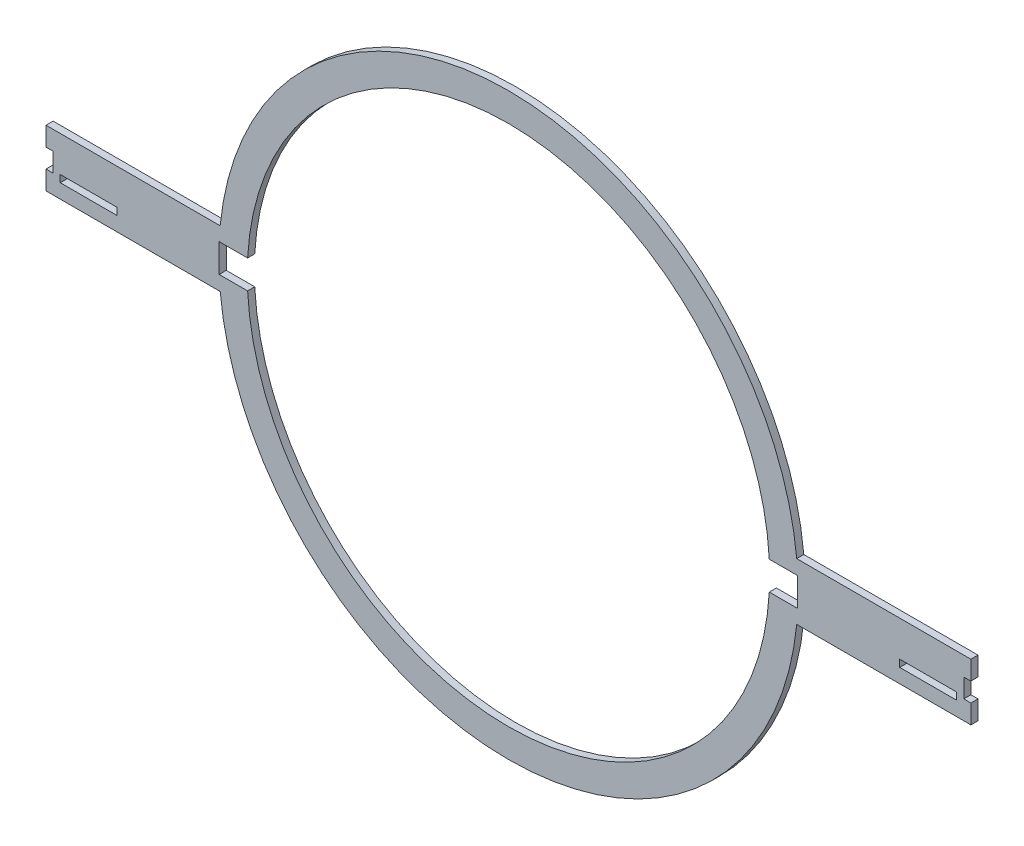
SolidWorks part; units mm, degrees
ref_plane "Front Plane" through (0, 0, 0) normal (0, 0, 1) x (1, 0, 0)
ref_plane "Top Plane" through (0, 0, 0) normal (0, 1, 0) x (1, 0, 0)
ref_plane "Right Plane" through (0, 0, 0) normal (1, 0, 0) x (0, 0, -1)
sketch "Sketch1" plane through (0, 0, 0) normal (0, 0, 1) x (1, 0, 0)
  line L0 (-128.648, -12.7) -> (-206.375, -12.7)
  line L1 (-206.375, -12.7) -> (-206.375, 12.7)
  line L2 (-206.375, 12.7) -> (-128.648, 12.7)
  line L3 (0, -55) -> (0, 55) construction
  line L4 (128.648, -12.7) -> (206.375, -12.7)
  line L5 (206.375, -12.7) -> (206.375, 12.7)
  line L6 (206.375, 12.7) -> (128.648, 12.7)
  circle A0 centre (0, 0) radius 116.5733
  circle A1 centre (0, 0) radius 129.2733
  point P6 (-206.375, 0)
  dimension "D1" = 233.1466
  dimension "D2" = 12.7
  dimension "D3" = 25.4
  dimension "D4" = 206.375
extrude "Boss-Extrude1" add sketch "Sketch1" along normal blind 3.175 contours A1 L2 L1 L0 | A1 A0 | A1 L4 L5 L6
sketch "Sketch2" plane through (0, 0, 3.175) normal (0, 0, 1) x (1, 0, 0)
  line L0 (-206.375, -12.7) -> (-206.375, 12.7) construction
  line L1 (-206.375, 4.2333) -> (-203.2, 4.2333)
  line L2 (-206.375, 4.2333) -> (-206.375, -4.2333)
  line L3 (-206.375, -4.2333) -> (-203.2, -4.2333)
  line L4 (-203.2, 4.2333) -> (-203.2, -4.2333)
  point P6 (-206.375, 0)
  dimension "D1" = 3.175
  dimension "D2" = 8.4667
extrude "Cut-Extrude1" cut sketch "Sketch2" against normal blind 3.175
mirror "Mirror1" about plane through (0, 0, 0) normal (1, 0, 0) of "Cut-Extrude1"
sketch "Sketch3" plane through (0, 0, 3.175) normal (0, 0, 1) x (1, 0, 0)
  line L0 (-116.4002, -6.35) -> (-129.1002, -6.35)
  line L1 (-129.1002, -6.35) -> (-129.1002, 6.35)
  line L2 (-129.1002, 6.35) -> (-116.4002, 6.35)
  circle A0 centre (0, 0) radius 116.5733 construction
  arc A1 (-116.4002, 6.35) -> (-116.4002, -6.35) centre (0, 0) ccw
  point P4 (-129.1002, 0)
  dimension "D1" = 12.7
  dimension "D2" = 12.7
extrude "Cut-Extrude6" cut sketch "Sketch3" against normal blind 3.175 contours A1 L0 L1 L2
mirror "Mirror2" about plane through (0, 0, 0) normal (1, 0, 0) of "Cut-Extrude6"
sketch "Sketch4" plane through (0, 0, 3.175) normal (0, 0, 1) x (1, 0, 0)
  line L1 (200.025, -3.175) -> (174.625, -3.175)
  line L2 (200.025, -3.175) -> (200.025, -6.35)
  line L3 (200.025, -6.35) -> (174.625, -6.35)
  line L4 (174.625, -3.175) -> (174.625, -6.35)
  line L5 (203.2, -4.2333) -> (203.2, 4.2333) construction
  line L6 (128.648, -12.7) -> (206.375, -12.7) construction
  point P5 (0, 0)
  dimension "D1" = 25.4
  dimension "D2" = 3.175
  dimension "D3" = 3.175
  dimension "D4" = 6.35
extrude "Cut-Extrude7" cut sketch "Sketch4" against normal blind 3.175
mirror "Mirror3" about plane through (0, 0, 0) normal (1, 0, 0) of "Cut-Extrude7"
